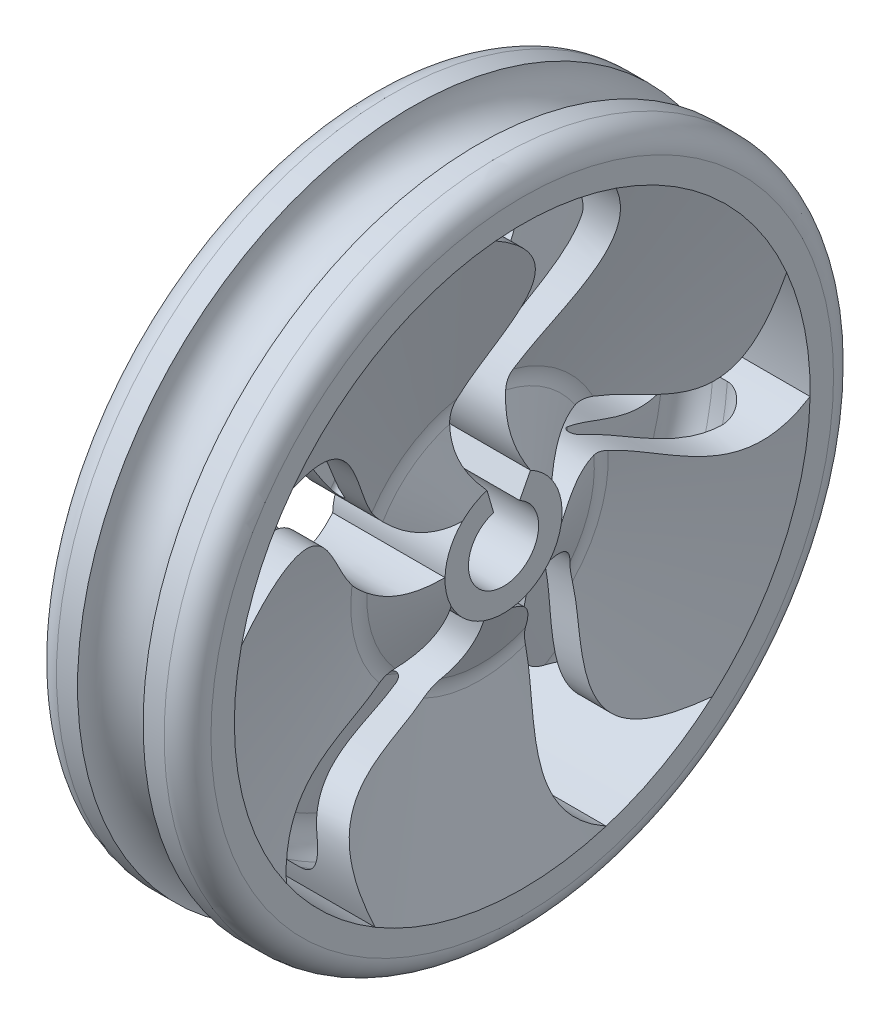
SolidWorks part; units mm, degrees
ref_plane "Alzado" through (0, 0, 0) normal (0, 0, 1) x (1, 0, 0)
ref_plane "Planta" through (0, 0, 0) normal (0, 1, 0) x (1, 0, 0)
ref_plane "Vista lateral" through (0, 0, 0) normal (1, 0, 0) x (0, 0, -1)
sketch "Croquis1" plane through (0, 0, 0) normal (0, 0, 1) x (1, 0, 0)
  line L1 (-1.4, 14.3) -> (-2.3, 14.3)
  line L2 (1.4, 14.3) -> (2.3, 14.3)
  line L3 (-3.3, 13.3) -> (-3.3, 12.3)
  line L4 (-3.3, 12.3) -> (-1.4776, 5.5074)
  line L6 (3.3, 12.3) -> (3.3, 13.3)
  line L7 (-0.2001, 11.6799) -> (0.4109, 11.6799)
  line L8 (1.3884, 10.4687) -> (0.3174, 5.5101)
  line L9 (-0.271, 5.5194) -> (-1.1837, 10.4996)
  line L10 (0, 0) -> (-2.3, 0)
  line L11 (-2.3, 0) -> (-2.3, 2.5)
  line L13 (2.5, 2.5) -> (2.5, 0)
  line L14 (2.5, 0) -> (0, 0)
  line L15 (-2.3, 2.5) -> (-1.4941, 4.9339)
  line L16 (2.5, 2.5) -> (1.519, 4.8607)
  line L18 (0.6478, 2.4146) -> (0.6707, 2.5)
  line L19 (1.4766, 5.5036) -> (3.3, 12.3)
  arc A0 (-1.4, 14.3) -> (1.4, 14.3) centre (0, 14.3) ccw
  arc A1 (-0.2001, 11.6799) -> (-1.1837, 10.4996) centre (-0.2001, 10.6799) ccw
  arc A2 (0.4109, 11.6799) -> (1.3884, 10.4687) centre (0.4109, 10.6799) cw
  arc A3 (0.3174, 5.5101) -> (-0.271, 5.5194) centre (0.0241, 5.5734) cw
  arc A4 (-2.3, 14.3) -> (-3.3, 13.3) centre (-2.3, 13.3) ccw
  arc A5 (3.3, 13.3) -> (2.3, 14.3) centre (2.3, 13.3) ccw
  arc A6 (-1.4776, 5.5074) -> (-1.4941, 4.9339) centre (-2.4434, 5.2483) cw
  arc A7 (1.4766, 5.5036) -> (1.519, 4.8607) centre (2.4424, 5.2445) ccw
  point P19 (0, 4.0408)
  dimension "D1" = 1
  dimension "D2" = 1
  dimension "D3" = 0.3
  dimension "D4" = 1
  dimension "D5" = 1
  dimension "D6" = 1
  dimension "D7" = 1
revolve "Revolución3" add sketch "Croquis1" angle 360 about L10
sketch "Croquis2" plane through (2.5, 0, 0) normal (1, 0, 0) x (0, 0, -1)
  circle A0 centre (0, 0) radius 12.3 construction
  arc A1 (1.1524, 2.2186) -> (-0.7043, 2.3987) centre (0, 0) ccw
  circle A2 centre (0, 0) radius 4.8607 construction
  arc A3 (4.0155, 11.6261) -> (-1.1351, 12.2475) centre (0, 0) ccw
  spline S0 degree 3 poles (1.1524, 2.2186) (-0.974, 6.0062) (6.3971, 7.2442) (4.0155, 11.6261) knots 0 0 0 0 1 1 1 1
  spline S1 degree 3 poles (-0.7043, 2.3987) (-4.0113, 6.2229) (5.571, 7.868) (-1.1351, 12.2475) knots 0 0 0 0 1 1 1 1
extrude "Cortar-Extruir1" cut sketch "Croquis2" against normal blind 10 and the other way blind 10
sketch "Croquis4" plane through (2.5, 0, 0) normal (1, 0, 0) x (0, 0, -1)
  line L0 (-0.4226, 1.4392) -> (-0.7043, 2.3987)
  line L1 (0.6914, 1.3311) -> (1.1524, 2.2186)
  arc A0 (-0.4226, 1.4392) -> (0.6914, 1.3311) centre (0, 0) ccw
  arc A1 (1.1524, 2.2186) -> (-0.7043, 2.3987) centre (0, 0) ccw
  dimension "D1" = 3
ref_axis "Eje3" through (2.5, 0, 0) along (-1, 0, 0)
pattern_circular "MatrizC3" count 5 over 360 about axis through (2.5, 0, 0) along (-1, 0, 0) of "Cortar-Extruir1"
extrude "Cortar-Extruir2" cut sketch "Croquis4" against normal blind 10
